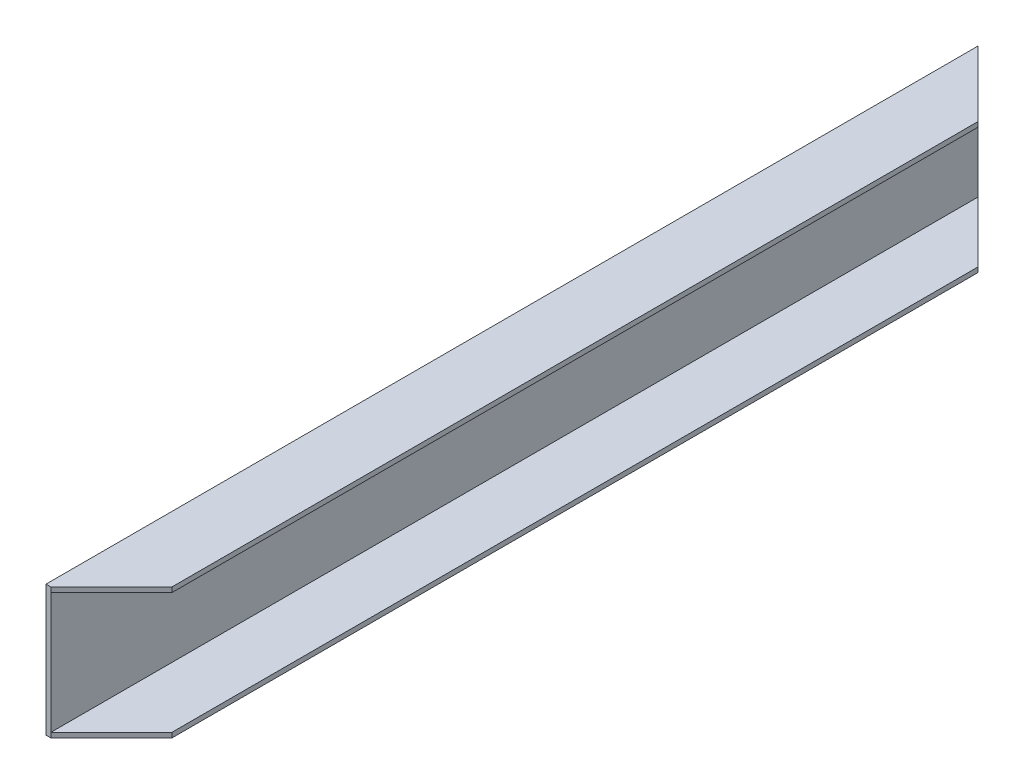
SolidWorks part; units mm, degrees
material "6063-O"
ref_plane "Plano frontal" through (0, 0, 0) normal (0, 0, 1) x (1, 0, 0)
ref_plane "Plano superior" through (0, 0, 0) normal (0, 1, 0) x (1, 0, 0)
ref_plane "Plano direito" through (0, 0, 0) normal (1, 0, 0) x (0, 0, -1)
sketch "Esboço1" plane through (0, 0, 0) normal (0, 0, 1) x (1, 0, 0)
  line L0 (0, 20) -> (0, -20)
  line L1 (-4.345, 0) -> (24.7582, 0) construction
  line L2 (0, 20) -> (20, 20)
  line L3 (0, -20) -> (20, -20)
  line L4 (20, 20) -> (20, 18.5)
  line L5 (20, 18.5) -> (1.5, 18.5)
  line L6 (1.5, 18.5) -> (1.5, -18.5)
  line L7 (20, -18.5) -> (1.5, -18.5)
  line L8 (20, -20) -> (20, -18.5)
  line L9 (1.5, 18.5) -> (0, 18.5) construction
  dimension "D1" = 40
  dimension "D2" = 20
  dimension "D3" = 1.5
extrude "Ressalto-extrusão1" add sketch "Esboço1" along normal mid plane 285
sketch "Esboço2" plane through (0, 20, 0) normal (0, 1, 0) x (1, 0, 0)
  line L0 (1.5, -142.5) -> (20, -124)
  line L1 (20, -142.5) -> (20, 142.5) construction
  line L2 (20, -124) -> (20, -142.5)
  line L3 (20, -142.5) -> (1.5, -142.5)
  line L4 (0, 142.5) -> (20, 122.5)
  line L5 (20, 122.5) -> (20, 142.5)
  line L6 (20, 142.5) -> (0, 142.5)
extrude "Corte-extrusão1" cut sketch "Esboço2" against normal mid plane 100
